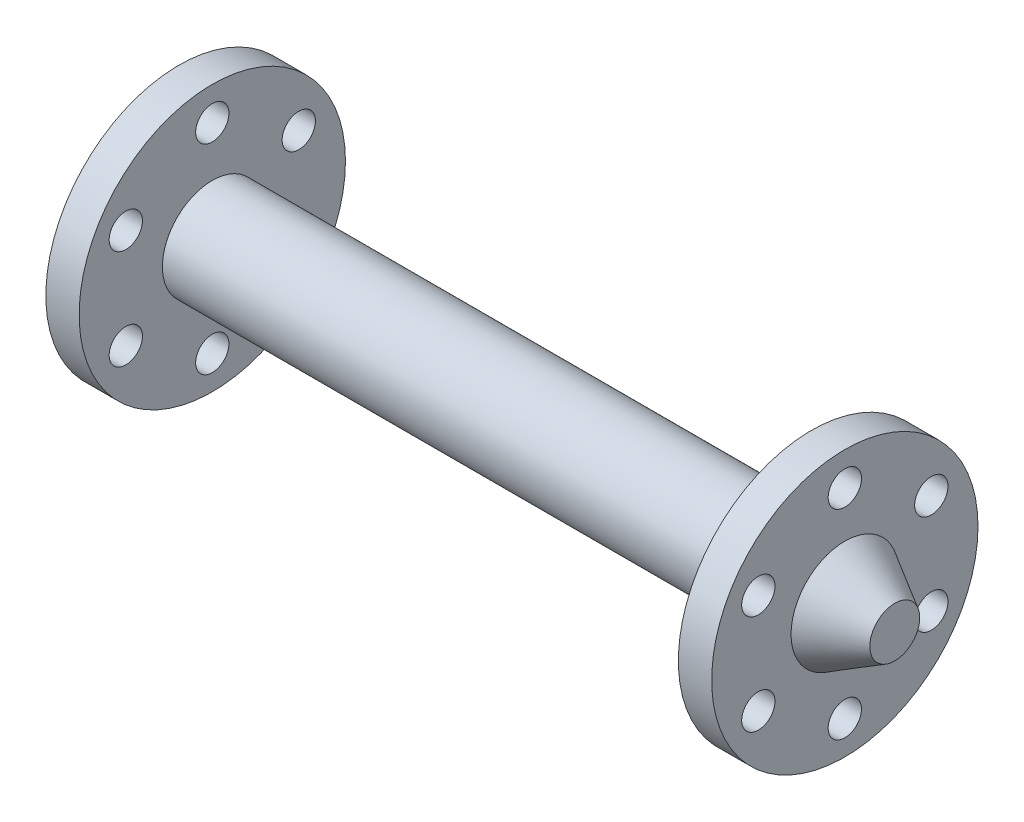
SolidWorks part; units mm, degrees
ref_plane "Front Plane" through (0, 0, 0) normal (0, 0, 1) x (1, 0, 0)
ref_plane "Top Plane" through (0, 0, 0) normal (0, 1, 0) x (1, 0, 0)
ref_plane "Right Plane" through (0, 0, 0) normal (1, 0, 0) x (0, 0, -1)
sketch "Sketch1" plane through (0, 0, 0) normal (0, 0, 1) x (1, 0, 0)
  line L0 (-89.0909, 0) -> (115.6818, 0) construction
  line L1 (0, 0) -> (0, 15)
  line L2 (0, 15) -> (30, 32.3205)
  line L3 (30, 32.3205) -> (30, 0)
  line L4 (30, 0) -> (0, 0)
  dimension "D1" = 15
  dimension "D2" = 30
  dimension "D3" = 30
revolve "Revolve1" add sketch "Sketch1" angle 360 about L0
sketch "Sketch3" plane through (30, 0, 0) normal (1, 0, 0) x (0, 0, -1)
  circle A0 centre (0, 0) radius 80
  dimension "D1" = 160
extrude "Boss-Extrude1" add sketch "Sketch3" along normal blind 20
sketch "Sketch4" plane through (30, 0, 0) normal (-1, 0, 0) x (0, 0, 1)
  circle A0 centre (0, 0) radius 60 construction
  circle A1 centre (0, 60) radius 10
  circle A2 centre (51.9615, 30) radius 10
  circle A3 centre (51.9615, -30) radius 10
  circle A4 centre (0, -60) radius 10
  circle A5 centre (-51.9615, -30) radius 10
  circle A6 centre (-51.9615, 30) radius 10
  point P17 (0, 0)
  dimension "D1" = 120
  dimension "D2" = 20
  dimension "D3" = 6
extrude "Cut-Extrude1" cut sketch "Sketch4" against normal through all
sketch "Sketch5" plane through (50, 0, 0) normal (1, 0, 0) x (0, 0, -1)
  circle A0 centre (0, 0) radius 30
  dimension "D1" = 60
extrude "Boss-Extrude2" add sketch "Sketch5" along normal blind 360
sketch "Sketch6" plane through (410, 0, 0) normal (1, 0, 0) x (0, 0, -1)
  circle A0 centre (0, 0) radius 80
  dimension "D1" = 160
extrude "Boss-Extrude3" add sketch "Sketch6" along normal blind 20
sketch "Sketch7" plane through (430, 0, 0) normal (1, 0, 0) x (0, 0, -1)
  circle A0 centre (0, 0) radius 60 construction
  circle A1 centre (0, 60) radius 10
  circle A2 centre (51.9615, 30) radius 10
  circle A3 centre (51.9615, -30) radius 10
  circle A4 centre (0, -60) radius 10
  circle A5 centre (-51.9615, -30) radius 10
  circle A6 centre (-51.9615, 30) radius 10
  point P17 (0, 0)
  dimension "D1" = 120
  dimension "D2" = 20
  dimension "D3" = 6
extrude "Cut-Extrude2" cut sketch "Sketch7" against normal blind 20
sketch "Sketch9" plane through (0, 0, 0) normal (0, 1, 0) x (1, 0, 0)
  line L0 (-124.816, 0) -> (588.9368, 0) construction
  line L1 (460, 15) -> (460, 0)
  line L2 (460, 0) -> (430, 0)
  line L3 (430, -80) -> (430, 80) construction
  line L4 (430, 0) -> (430, 32.3205)
  line L5 (430, 32.3205) -> (460, 15)
  dimension "D1" = 15
  dimension "D2" = 30
  dimension "D3" = 30
revolve "Revolve2" add sketch "Sketch9" angle 360 about L0
